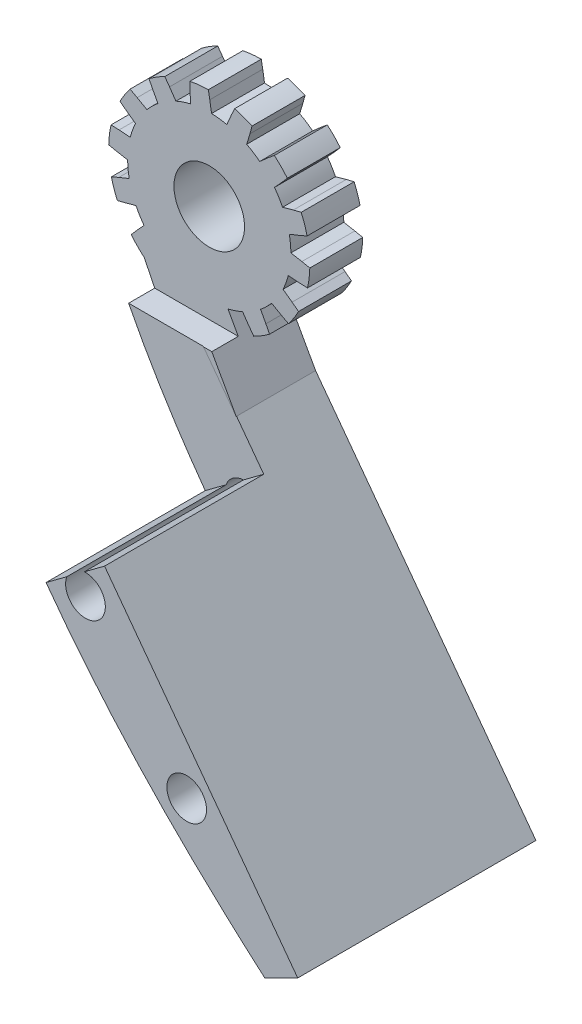
SolidWorks part; units mm, degrees
ref_plane "Front Plane" through (0, 0, 0) normal (0, 0, 1) x (1, 0, 0)
ref_plane "Top Plane" through (0, 0, 0) normal (0, 1, 0) x (1, 0, 0)
ref_plane "Right Plane" through (0, 0, 0) normal (1, 0, 0) x (0, 0, -1)
sketch "Sketch2" plane through (0, 0, 0) normal (0, 0, 1) x (1, 0, 0)
  line L595 (17.593, 3.4479) -> (18.4327, 3.8121)
  line L596 (16.415, 2.9762) -> (17.593, 3.4479)
  line L597 (15.6491, 5.2416) -> (16.8717, 5.5815)
  line L598 (16.8717, 5.5815) -> (17.7601, 5.8015)
  line L599 (5.2228, 10.175) -> (5.1635, 11.4426)
  line L600 (5.1635, 11.4426) -> (5.1467, 12.3577)
  line L601 (11.588, 9.3895) -> (11.9537, 10.6047)
  line L602 (11.9537, 10.6047) -> (12.1925, 11.4882)
  line L603 (9.3394, 10.2032) -> (9.8359, 11.371)
  line L604 (9.8359, 11.371) -> (10.2178, 12.2028)
  line L605 (14.7334, 6.7337) -> (15.5901, 7.6699)
  line L606 (15.5901, 7.6699) -> (16.1886, 8.3623)
  line L607 (13.0605, 8.4425) -> (14.0145, 9.2792)
  line L608 (14.0145, 9.2792) -> (14.7195, 9.8629)
  line L609 (-1.907, 1.1079) -> (-3.156, 1.3322)
  line L610 (-3.156, 1.3322) -> (-4.0519, 1.5194)
  line L611 (0.2752, 7.1388) -> (-0.8281, 7.7657)
  line L612 (-0.8281, 7.7657) -> (-1.6364, 8.1951)
  line L613 (-1.0184, 5.1275) -> (-2.0464, 5.8715)
  line L614 (-2.0464, 5.8715) -> (-2.7724, 6.4289)
  line L615 (3.5643, 9.6143) -> (2.8423, 10.6578)
  line L616 (2.8423, 10.6578) -> (2.3004, 11.3954)
  line L617 (1.5262, 8.3635) -> (0.9228, 9.4798)
  line L618 (0.9228, 9.4798) -> (0.5105, 10.297)
  line L619 (7.6018, 10.4176) -> (7.4041, 11.6711)
  line L620 (7.4041, 11.6711) -> (7.2358, 12.5707)
  line L621 (-0.0478, -4.3913) -> (-0.9045, -5.3274)
  line L622 (-0.9045, -5.3274) -> (-1.503, -6.0199)
  line L623 (1.6251, -6.1) -> (0.6711, -6.9367)
  line L624 (0.6711, -6.9367) -> (-0.0339, -7.5204)
  line L625 (-1.7294, -0.6337) -> (-2.9074, -1.1055)
  line L626 (-2.9074, -1.1055) -> (-3.7471, -1.4697)
  line L627 (-0.9635, -2.8991) -> (-2.1861, -3.239)
  line L628 (-2.1861, -3.239) -> (-3.0745, -3.459)
  line L629 (-1.6141, 3.4813) -> (-2.8801, 3.5674)
  line L630 (-2.8801, 3.5674) -> (-3.7947, 3.6036)
  line L631 (13.1594, -6.0211) -> (13.7628, -7.1374)
  line L632 (13.7628, -7.1374) -> (14.1751, -7.9546)
  line L633 (7.0838, -8.0751) -> (7.2815, -9.3286)
  line L634 (7.2815, -9.3286) -> (7.4497, -10.2283)
  line L635 (9.4628, -7.8326) -> (9.5221, -9.1001)
  line L636 (9.5221, -9.1001) -> (9.5389, -10.0152)
  line L637 (3.0976, -7.0471) -> (2.7319, -8.2622)
  line L638 (2.7319, -8.2622) -> (2.4931, -9.1458)
  line L639 (5.3462, -7.8607) -> (4.8497, -9.0285)
  line L640 (4.8497, -9.0285) -> (4.4678, -9.8603)
  line L641 (16.2997, -1.1388) -> (17.5657, -1.2249)
  line L642 (17.5657, -1.2249) -> (18.4803, -1.2611)
  line L643 (16.5926, 1.2345) -> (17.8416, 1.0103)
  line L644 (17.8416, 1.0103) -> (18.7375, 0.8231)
  line L645 (14.4104, -4.7963) -> (15.5137, -5.4232)
  line L646 (15.5137, -5.4232) -> (16.322, -5.8526)
  line L647 (15.704, -2.7851) -> (16.732, -3.529)
  line L648 (16.732, -3.529) -> (17.458, -4.0864)
  line L649 (11.1213, -7.2719) -> (11.8433, -8.3154)
  line L650 (11.8433, -8.3154) -> (12.3852, -9.053)
  arc A45 (12.3852, -9.053) -> (14.1751, -7.9546) centre (7.3428, 1.1712) ccw
  arc A46 (7.4497, -10.2283) -> (9.5389, -10.0152) centre (7.3428, 1.1712) ccw
  arc A48 (2.4931, -9.1458) -> (4.4678, -9.8603) centre (7.3428, 1.1712) ccw
  arc A50 (-1.503, -6.0199) -> (-0.0339, -7.5204) centre (7.3428, 1.1712) ccw
  arc A51 (5.3462, -7.8607) -> (7.0838, -8.0751) centre (7.3428, 1.1712) ccw
  arc A52 (-3.7471, -1.4697) -> (-3.0745, -3.459) centre (7.3428, 1.1712) ccw
  arc A53 (-3.7947, 3.6036) -> (-4.0519, 1.5194) centre (7.3428, 1.1712) ccw
  arc A54 (-1.6364, 8.1951) -> (-2.7724, 6.4289) centre (7.3428, 1.1712) ccw
  arc A55 (2.3004, 11.3954) -> (0.5105, 10.297) centre (7.3428, 1.1712) ccw
  arc A56 (7.2358, 12.5707) -> (5.1467, 12.3577) centre (7.3428, 1.1712) ccw
  arc A57 (12.1925, 11.4882) -> (10.2178, 12.2028) centre (7.3428, 1.1712) ccw
  arc A58 (16.1886, 8.3623) -> (14.7195, 9.8629) centre (7.3428, 1.1712) ccw
  arc A59 (18.4327, 3.8121) -> (17.7601, 5.8015) centre (7.3428, 1.1712) ccw
  arc A60 (18.4803, -1.2611) -> (18.7375, 0.8231) centre (7.3428, 1.1712) ccw
  arc A61 (16.322, -5.8526) -> (17.458, -4.0864) centre (7.3428, 1.1712) ccw
  arc A62 (1.6251, -6.1) -> (3.0976, -7.0471) centre (7.3428, 1.1712) ccw
  arc A63 (-0.9635, -2.8991) -> (-0.0478, -4.3913) centre (7.3428, 1.1712) ccw
  arc A64 (-1.907, 1.1079) -> (-1.7294, -0.6337) centre (7.3428, 1.1712) ccw
  arc A65 (-1.0184, 5.1275) -> (-1.6141, 3.4813) centre (7.3428, 1.1712) ccw
  arc A66 (1.5262, 8.3635) -> (0.2752, 7.1388) centre (7.3428, 1.1712) ccw
  arc A67 (5.2228, 10.175) -> (3.5643, 9.6143) centre (7.3428, 1.1712) ccw
  arc A68 (9.3394, 10.2032) -> (7.6018, 10.4176) centre (7.3428, 1.1712) ccw
  arc A69 (13.0605, 8.4425) -> (11.588, 9.3895) centre (7.3428, 1.1712) ccw
  arc A70 (15.6491, 5.2416) -> (14.7334, 6.7337) centre (7.3428, 1.1712) ccw
  arc A71 (16.5926, 1.2345) -> (16.415, 2.9762) centre (7.3428, 1.1712) ccw
  arc A72 (15.704, -2.7851) -> (16.2997, -1.1388) centre (7.3428, 1.1712) ccw
  arc A73 (13.1594, -6.0211) -> (14.4104, -4.7963) centre (7.3428, 1.1712) ccw
  arc A74 (9.4628, -7.8326) -> (11.1213, -7.2719) centre (7.3428, 1.1712) ccw
extrude "Boss-Extrude1" add sketch "Sketch2" against normal blind 7 and the other way blind 2
sketch "Sketch5" plane through (0, 0, 2) normal (0, 0, 1) x (1, 0, 0)
  line L1 (11.4711, 11.5) -> (18.1778, 11.5) construction
  line L2 (-0.0339, -7.5204) -> (0.6711, -6.9367) construction
  line L6 (34.628, -50.4079) -> (38.3692, -48.5518)
  line L7 (-0.0339, -7.5204) -> (0.8657, -2.8432)
  line L8 (38.3692, -48.5518) -> (13.394, -14.9204)
  line L9 (0.8657, -2.8432) -> (9.4628, -7.8326)
  arc A1 (9.4628, -7.8326) -> (11.1213, -7.2719) centre (7.3428, 1.1712) ccw construction
  arc A2 (-1.503, -6.0199) -> (-0.0339, -7.5204) centre (7.3428, 1.1712) ccw construction
  spline S0 degree 1 poles (13.394, -14.9204) (9.4628, -7.8326) knots 0 0 1 1
  spline S1 degree 3 poles (34.628, -50.4079) (20.7375, -38.3435) (7.9572, -24.2645) (-0.0339, -7.5204) knots 0 0 0 0 1 1 1 1
extrude "Boss-Extrude3" add sketch "Sketch5" against normal up to surface (9 mm away) up to face at (7.3428, 1.1712, -7)
sketch "Sketch6" plane through (0, 0, -7) normal (0, 0, -1) x (-1, 0, 0)
  circle A2 centre (-7.3428, 1.1712) radius 4
  dimension "D1" = 8
extrude "Cut-Extrude1" cut sketch "Sketch6" against normal blind 18
sketch "Sketch7" plane through (0, 0, 2) normal (0, 0, 1) x (1, 0, 0)
  line L49 (34.628, -50.4079) -> (38.3692, -48.5518)
  line L50 (38.3692, -48.5518) -> (13.394, -14.9204)
  line L51 (13.394, -14.9204) -> (9.4628, -7.8326)
  line L52 (11.1213, -7.2719) -> (11.8433, -8.3154)
  line L53 (11.8433, -8.3154) -> (12.3852, -9.053)
  line L54 (14.1751, -7.9546) -> (13.7628, -7.1374)
  line L55 (13.7628, -7.1374) -> (13.1594, -6.0211)
  line L56 (14.4104, -4.7963) -> (15.5137, -5.4232)
  line L57 (15.5137, -5.4232) -> (16.322, -5.8526)
  line L58 (17.458, -4.0864) -> (16.732, -3.529)
  line L59 (16.732, -3.529) -> (15.704, -2.7851)
  line L60 (16.2997, -1.1388) -> (17.5657, -1.2249)
  line L61 (17.5657, -1.2249) -> (18.4803, -1.2611)
  line L62 (18.7375, 0.8231) -> (17.8416, 1.0103)
  line L63 (17.8416, 1.0103) -> (16.5926, 1.2345)
  line L64 (16.415, 2.9762) -> (17.593, 3.4479)
  line L65 (17.593, 3.4479) -> (18.4327, 3.8121)
  line L66 (17.7601, 5.8015) -> (16.8717, 5.5815)
  line L67 (16.8717, 5.5815) -> (15.6491, 5.2416)
  line L68 (14.7334, 6.7337) -> (15.5901, 7.6699)
  line L69 (15.5901, 7.6699) -> (16.1886, 8.3623)
  line L70 (14.7195, 9.8629) -> (14.0145, 9.2792)
  line L71 (14.0145, 9.2792) -> (13.0605, 8.4425)
  line L72 (11.588, 9.3895) -> (11.9537, 10.6047)
  line L73 (11.9537, 10.6047) -> (12.1925, 11.4882)
  line L74 (10.2178, 12.2028) -> (9.8359, 11.371)
  line L75 (9.8359, 11.371) -> (9.3394, 10.2032)
  line L76 (7.6018, 10.4176) -> (7.4041, 11.6711)
  line L77 (7.4041, 11.6711) -> (7.2358, 12.5707)
  line L78 (5.1467, 12.3577) -> (5.1635, 11.4426)
  line L79 (5.1635, 11.4426) -> (5.2228, 10.175)
  line L80 (3.5643, 9.6143) -> (2.8423, 10.6578)
  line L81 (2.8423, 10.6578) -> (2.3004, 11.3954)
  line L82 (0.5105, 10.297) -> (0.9228, 9.4798)
  line L83 (0.9228, 9.4798) -> (1.5262, 8.3635)
  line L84 (0.2752, 7.1388) -> (-0.8281, 7.7657)
  line L85 (-0.8281, 7.7657) -> (-1.6364, 8.1951)
  line L86 (-2.7724, 6.4289) -> (-2.0464, 5.8715)
  line L87 (-2.0464, 5.8715) -> (-1.0184, 5.1275)
  line L88 (-1.6141, 3.4813) -> (-2.8801, 3.5674)
  line L89 (-2.8801, 3.5674) -> (-3.7947, 3.6036)
  line L90 (-4.0519, 1.5194) -> (-3.156, 1.3322)
  line L91 (-3.156, 1.3322) -> (-1.907, 1.1079)
  line L92 (-1.7294, -0.6337) -> (-2.9074, -1.1055)
  line L93 (-2.9074, -1.1055) -> (-3.7471, -1.4697)
  line L94 (-3.0745, -3.459) -> (-2.1861, -3.239)
  line L95 (-2.1861, -3.239) -> (-0.9635, -2.8991)
  line L96 (-0.0478, -4.3913) -> (-0.9045, -5.3274)
  line L97 (-0.9045, -5.3274) -> (-1.503, -6.0199)
  line L98 (34.628, -50.4079) -> (38.3692, -48.5518)
  line L99 (38.3692, -48.5518) -> (13.394, -14.9204)
  arc A24 (-1.503, -6.0199) -> (-0.0339, -7.5204) centre (7.3428, 1.1712) ccw
  arc A25 (9.4628, -7.8326) -> (11.1213, -7.2719) centre (7.3428, 1.1712) ccw
  arc A26 (12.3852, -9.053) -> (14.1751, -7.9546) centre (7.3428, 1.1712) ccw
  arc A27 (13.1594, -6.0211) -> (14.4104, -4.7963) centre (7.3428, 1.1712) ccw
  arc A28 (16.322, -5.8526) -> (17.458, -4.0864) centre (7.3428, 1.1712) ccw
  arc A29 (15.704, -2.7851) -> (16.2997, -1.1388) centre (7.3428, 1.1712) ccw
  arc A30 (18.4803, -1.2611) -> (18.7375, 0.8231) centre (7.3428, 1.1712) ccw
  arc A31 (16.5926, 1.2345) -> (16.415, 2.9762) centre (7.3428, 1.1712) ccw
  arc A32 (18.4327, 3.8121) -> (17.7601, 5.8015) centre (7.3428, 1.1712) ccw
  arc A33 (15.6491, 5.2416) -> (14.7334, 6.7337) centre (7.3428, 1.1712) ccw
  arc A34 (16.1886, 8.3623) -> (14.7195, 9.8629) centre (7.3428, 1.1712) ccw
  arc A35 (13.0605, 8.4425) -> (11.588, 9.3895) centre (7.3428, 1.1712) ccw
  arc A36 (12.1925, 11.4882) -> (10.2178, 12.2028) centre (7.3428, 1.1712) ccw
  arc A37 (9.3394, 10.2032) -> (7.6018, 10.4176) centre (7.3428, 1.1712) ccw
  arc A38 (7.2358, 12.5707) -> (5.1467, 12.3577) centre (7.3428, 1.1712) ccw
  arc A39 (5.2228, 10.175) -> (3.5643, 9.6143) centre (7.3428, 1.1712) ccw
  arc A40 (2.3004, 11.3954) -> (0.5105, 10.297) centre (7.3428, 1.1712) ccw
  arc A41 (1.5262, 8.3635) -> (0.2752, 7.1388) centre (7.3428, 1.1712) ccw
  arc A42 (-1.6364, 8.1951) -> (-2.7724, 6.4289) centre (7.3428, 1.1712) ccw
  arc A43 (-1.0184, 5.1275) -> (-1.6141, 3.4813) centre (7.3428, 1.1712) ccw
  arc A44 (-3.7947, 3.6036) -> (-4.0519, 1.5194) centre (7.3428, 1.1712) ccw
  arc A45 (-1.907, 1.1079) -> (-1.7294, -0.6337) centre (7.3428, 1.1712) ccw
  arc A46 (-3.7471, -1.4697) -> (-3.0745, -3.459) centre (7.3428, 1.1712) ccw
  arc A47 (-0.9635, -2.8991) -> (-0.0478, -4.3913) centre (7.3428, 1.1712) ccw
  spline S0 degree 2 poles (7.978, -21.3451) (8.1121, -15.9213) (13.394, -14.9204) knots 0 0 0 1 1 1
  spline S1 degree 3 poles (2689.3147, 1264.9891) (-3237.4149, -692.61) (3465.2731, 248.2767) (-2933.8872, -462.9976) knots -8.084515 -8.084515 -8.084515 -8.084515 11.039067 11.039067 11.039067 11.039067 only from (-0.0339, -7.5204) to (34.628, -50.4079)
  spline S2 degree 3 poles (7.978, -21.3451) (15.4138, -32.2101) (24.7396, -41.8194) (34.628, -50.4079) knots 0.288119 0.288119 0.288119 0.288119 1 1 1 1
  dimension "D1" = 0
extrude "Boss-Extrude4" add sketch "Sketch7" along normal blind 18
sketch "Sketch8" plane through (0, 0, -7) normal (0, 0, -1) x (-1, 0, 0)
  circle A2 centre (-14.3128, -23.0208) radius 2.25
  circle A3 centre (-25.7856, -37.2154) radius 2.25
extrude "Cut-Extrude2" cut sketch "Sketch8" against normal through all
sketch "Sketch9" plane through (0, 0, 0) normal (1, 0, 0) x (0, 0, -1)
  line L0 (7, 3.8121) -> (7, 5.8015) construction
  line L1 (-9.3233, 17.5423) -> (1, 17.5423)
  line L2 (-9.3233, 17.5423) -> (-9.3233, -9.939)
  line L3 (-9.3233, -9.939) -> (1, -9.939)
  line L4 (1, 17.5423) -> (1, -9.939)
  dimension "D1" = 6
extrude "Cut-Extrude3" cut sketch "Sketch9" along normal through all and the other way through all
sketch "Sketch10" plane through (1.4914, 1.1075, 0) normal (0.8028, 0.5962, 0) x (0, 0, -1)
  line L0 (-2, -19.1331) -> (-20, -19.1331) construction
  line L1 (-27.1888, -7.44) -> (-1.9586, -7.44)
  line L2 (-27.1888, -7.44) -> (-27.1888, -25.1331)
  line L3 (-27.1888, -25.1331) -> (-1.9586, -25.1331)
  line L4 (-1.9586, -7.44) -> (-1.9586, -25.1331)
  dimension "D1" = 6
extrude "Cut-Extrude4" cut sketch "Sketch10" against normal through all
